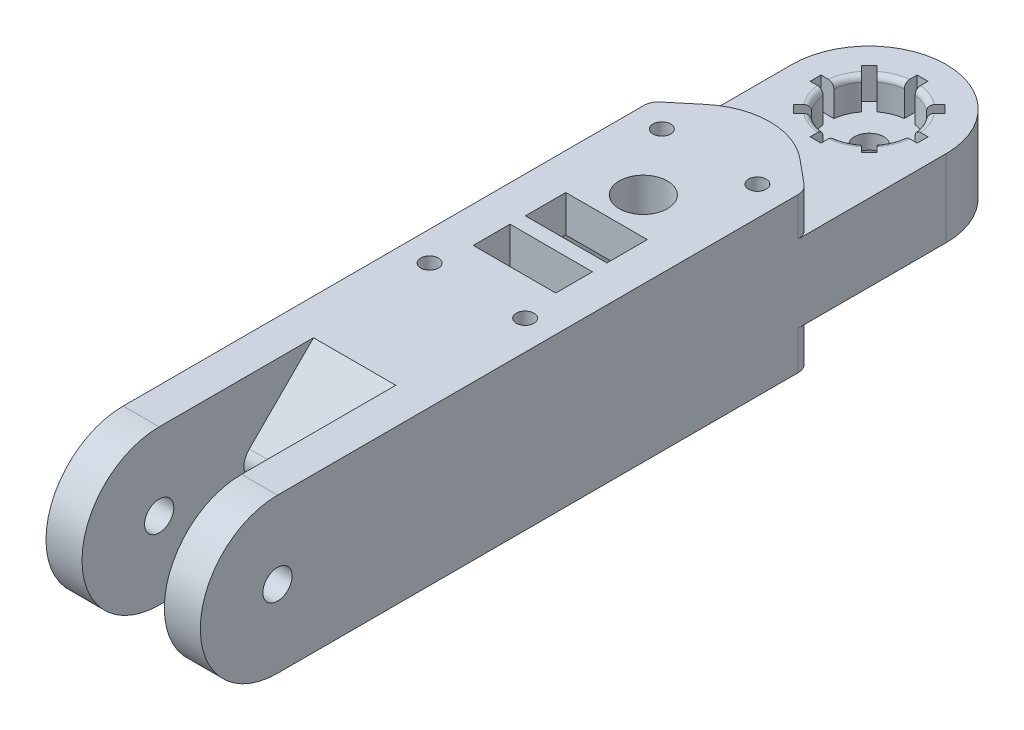
SolidWorks part; units mm, degrees
ref_plane "Front Plane" through (0, 0, 0) normal (0, 0, 1) x (1, 0, 0)
ref_plane "Top Plane" through (0, 0, 0) normal (0, 1, 0) x (1, 0, 0)
ref_plane "Right Plane" through (0, 0, 0) normal (1, 0, 0) x (0, 0, -1)
sketch "Sketch1" plane through (0, 0, 0) normal (0, 0, 1) x (1, 0, 0)
  line L1 (-21, 21) -> (21, 21)
  line L2 (-21, 21) -> (-21, -21)
  line L3 (-21, -21) -> (21, -21)
  line L4 (21, 21) -> (21, -21)
  line L5 (-21, 21) -> (21, -21) construction
  line L6 (-21, -21) -> (21, 21) construction
  point P0 (0, 0)
  dimension "D1" = 42
  dimension "D2" = 42
extrude "Boss-Extrude1" add sketch "Sketch1" along normal blind 140
ref_plane "Plane1" through (0, 0, 140) normal (0, 0, 1) x (1, 0, 0)
sketch "Sketch2" plane through (0, 0, 140) normal (0, 0, 1) x (1, 0, 0)
  line L0 (-21, -21) -> (21, -21) construction
  line L1 (-21, 21) -> (-11.2, 21)
  line L2 (-21, 21) -> (-21, -21)
  line L3 (-21, -21) -> (-11.2, -21)
  line L4 (-11.2, 21) -> (-11.2, -21)
  line L5 (21, 21) -> (-21, 21) construction
  line L6 (21, -21) -> (11.2, -21)
  line L7 (21, -21) -> (21, 21)
  line L8 (21, 21) -> (11.2, 21)
  line L9 (11.2, -21) -> (11.2, 21)
  dimension "D1" = 9.8
  dimension "D2" = 9.8
extrude "Boss-Extrude2" add sketch "Sketch2" along normal blind 21
ref_plane "Plane2" through (-11.2, 0, 0) normal (1, 0, 0) x (0, 0, -1)
sketch "Sketch3" plane through (-11.2, 0, 0) normal (1, 0, 0) x (0, 0, -1)
  line L0 (-161, -21) -> (-161, 21)
  arc A0 (-161, -21) -> (-161, 21) centre (-161, 0) cw
  dimension "D1" = 21
ref_plane "Plane3" through (0, -21, 0) normal (0, -1, 0) x (-1, 0, 0)
ref_plane "Plane4" through (11.2, 0, 0) normal (-1, 0, 0) x (0, 0, 1)
sketch "Sketch5" plane through (11.2, 0, 0) normal (-1, 0, 0) x (0, 0, 1)
  line L0 (161, 21) -> (161, -21)
  line L4 (140, 21) -> (140, -21)
  line L5 (140, -21) -> (161, -21)
  line L6 (161, -21) -> (161, 21)
  line L7 (161, 21) -> (140, 21)
  line L8 (140, 21) -> (140, -21)
  line L9 (140, -21) -> (161, -21)
  line L11 (161, 21) -> (140, 21)
  arc A0 (161, 21) -> (161, -21) centre (161, 0) cw
  dimension "D1" = 21
  dimension "D2" = 0
extrude "Boss-Extrude4" add sketch "Sketch5" against normal blind 9.8 contours A0 L0
extrude "Boss-Extrude5" add sketch "Sketch3" against normal blind 9.8
sketch "Sketch6" plane through (11.2, 0, 0) normal (-1, 0, 0) x (0, 0, 1)
  line L0 (161, -21) -> (161, 21) construction
  circle A0 centre (161, 0) radius 3.975
  dimension "D1" = 7.95
extrude "Cut-Extrude1" cut sketch "Sketch6" against normal through all
ref_plane "Plane5" through (-11.2, 0, 0) normal (1, 0, 0) x (0, 0, -1)
sketch "Sketch8" plane through (-11.2, 0, 0) normal (1, 0, 0) x (0, 0, -1)
  line L0 (-161, -21) -> (-161, 21) construction
  circle A0 centre (-161, 0) radius 3.975
  dimension "D1" = 7.95
extrude "Cut-Extrude2" cut sketch "Sketch8" against normal through all
ref_plane "Plane6" through (0, 0, 0) normal (0, 0, -1) x (-1, 0, 0)
sketch "Sketch9" plane through (0, 0, 0) normal (0, 0, -1) x (-1, 0, 0)
  line L0 (21, 21) -> (21, -21) construction
  line L1 (21, 10.5) -> (-21, 10.5)
  line L2 (21, 10.5) -> (21, -10.5)
  line L3 (21, -10.5) -> (-21, -10.5)
  line L4 (-21, 10.5) -> (-21, -10.5)
  line L5 (-21, -21) -> (-21, 21) construction
  line L6 (-21, 21) -> (21, 21) construction
  line L7 (21, -21) -> (-21, -21) construction
  dimension "D1" = 10.5
  dimension "D2" = 10.5
extrude "Boss-Extrude6" add sketch "Sketch9" along normal blind 21
ref_plane "Plane7" through (0, -10.5, 0) normal (0, -1, 0) x (-1, 0, 0)
sketch "Sketch10" plane through (0, -10.5, 0) normal (0, -1, 0) x (-1, 0, 0)
  line L0 (-21, 21) -> (21, 21)
  arc A0 (-21, 21) -> (21, 21) centre (0, 21) cw
  dimension "D1" = 21
extrude "Boss-Extrude7" add sketch "Sketch10" against normal blind 21
sketch "Sketch11" plane through (0, -10.5, 0) normal (0, -1, 0) x (-1, 0, 0)
  line L0 (21, 21) -> (-21, 21) construction
  circle A0 centre (0, 21) radius 11.35
  dimension "D1" = 22.7
extrude "Cut-Extrude3" cut sketch "Sketch11" against normal blind 8.5
ref_plane "Plane8" through (11.2, 0, 0) normal (-1, 0, 0) x (0, 0, 1)
sketch "Sketch16" plane through (11.2, 0, 0) normal (-1, 0, 0) x (0, 0, 1)
  line L0 (140, 21) -> (140, 0)
  line L1 (140, 21) -> (140, -21) construction
  line L2 (140, 0) -> (140, -21)
  line L3 (140, -21) -> (119, -21)
  line L4 (119, -21) -> (140, 0)
  line L5 (140, 21) -> (119, 21)
  line L6 (119, 21) -> (140, 0)
  line L7 (161, 0) -> (140, 0) construction
  dimension "D1" = 21
  dimension "D2" = 21
extrude "Cut-Extrude4" cut sketch "Sketch16" along normal blind 22.4 contours L0 L5 L6 | L2 L3 L4
fillet "Fillet1" radius 5 1 edges at (0, 0, 140)
ref_plane "Plane9" through (0, -10.5, 0) normal (0, -1, 0) x (-1, 0, 0)
ref_plane "Plane10" through (0, 10.5, 0) normal (0, 1, 0) x (1, 0, 0)
sketch "Sketch18" plane through (0, 10.5, 0) normal (0, 1, 0) x (1, 0, 0)
  line L0 (21, 21) -> (-21, 21) construction
  circle A0 centre (0, 21) radius 11.1605
  dimension "D1" = 22.321
extrude "Cut-Extrude5" cut sketch "Sketch18" against normal blind 8.5
sketch "Sketch19" plane through (0, -2, 0) normal (0, -1, 0) x (1, 0, 0)
  circle A0 centre (0, -21) radius 3.975
  dimension "D1" = 7.95
extrude "Cut-Extrude6" cut sketch "Sketch19" against normal blind 8.5
fillet "Fillet4" radius 1.5 1 edges at (11.35, -10.5, -21)
fillet "Fillet5" radius 1.5 1 edges at (-11.1605, 10.5, -21)
sketch "Sketch20" plane through (0, 10.5, 0) normal (0, 1, 0) x (1, 0, 0)
  line L1 (-1.48, 35.5655) -> (1.48, 35.5655)
  line L2 (-1.48, 35.5655) -> (-1.48, 31.7555)
  line L3 (-1.48, 31.7555) -> (1.48, 31.7555)
  line L4 (1.48, 35.5655) -> (1.48, 31.7555)
  line L5 (-1.48, 35.5655) -> (1.48, 31.7555) construction
  line L6 (-1.48, 31.7555) -> (1.48, 35.5655) construction
  circle A0 centre (0, 21) radius 12.6605 construction
  point P0 (0, 33.6605)
  dimension "D1" = 2.96
  dimension "D2" = 3.81
extrude "Cut-Extrude7" cut sketch "Sketch20" against normal blind 8.5
pattern_circular "CirPattern1" count 8 over 360 about axis through (0, 0, -21) along (0, 1, 0) of "Cut-Extrude7"
ref_plane "Plane11" through (0, 0, 0) normal (0, 1, 0) x (1, 0, 0)
mirror "Mirror1" about plane through (0, 0, 0) normal (0, 1, 0) of "CirPattern1", "Cut-Extrude7"
sketch "Sketch25" plane through (0, -21, 0) normal (0, -1, 0) x (1, 0, 0)
  line L0 (0, 0) -> (0, 119) construction
  line L2 (-21, 0) -> (21, 0) construction
  line L3 (17, 78.5) -> (-17, 78.5)
  line L4 (17, 78.5) -> (17, 29.5)
  line L5 (17, 29.5) -> (-17, 29.5)
  line L6 (-17, 78.5) -> (-17, 29.5)
  line L7 (17, 78.5) -> (-17, 29.5) construction
  line L8 (17, 29.5) -> (-17, 78.5) construction
  point P5 (0, 54)
  dimension "D1" = 34
  dimension "D2" = 49
  dimension "D3" = 54
extrude "Cut-Extrude11" cut sketch "Sketch25" against normal blind 32 contours L3 L6 L5 L4
sketch "Sketch26" plane through (0, -21, 0) normal (0, -1, 0) x (1, 0, 0)
  line L0 (0, 29.5) -> (0, 18.4) construction
  line L1 (17, 29.5) -> (-17, 29.5)
  line L2 (17, 29.5) -> (17, 26.5)
  line L3 (17, 26.5) -> (-17, 26.5)
  line L4 (-17, 29.5) -> (-17, 26.5)
  line L5 (-17, 26.5) -> (17, 26.5)
  line L6 (-17, 26.5) -> (-17, 18.4)
  line L7 (-17, 18.4) -> (17, 18.4)
  line L8 (17, 26.5) -> (17, 18.4)
  line M6 (17, 29.5) -> (-17, 29.5)
  line M7 (-21, 0) -> (21, 0)
  dimension "D1" = 3
  dimension "D2" = 8.1
extrude "Cut-Extrude12" cut sketch "Sketch26" against normal blind 27 contours L3 L0 L8 M7 | L0 L3 L2 M6 | L0 L1 L4 L5 | L0 L5 L6 M7 | L0 L6 L7 M7 | L0 L7 L8 M7
sketch "Sketch30" plane through (0, 6, 0) normal (0, -1, 0) x (1, 0, 0)
  line L0 (0, 29.5) -> (0, 18.4) construction
  line L1 (17, 29.5) -> (-17, 29.5) construction
  line L2 (-17, 18.4) -> (17, 18.4) construction
  line L3 (-17, 29.5) -> (-17, 18.4) construction
  circle A0 centre (-13, 22.4) radius 4
  circle A1 centre (-13, 22.4) radius 2.4
  dimension "D1" = 8
  dimension "D2" = 4.8
extrude "Cut-Extrude13" cut sketch "Sketch30" against normal through all contours A1
ref_plane "Plane12" through (0, 0, 0) normal (-1, 0, 0) x (0, 0, 1)
mirror "Mirror9" about plane through (0, 0, 0) normal (-1, 0, 0) of "Cut-Extrude13"
ref_plane "Plane13" through (0, 0, 54) normal (0, 0, 1) x (1, 0, 0)
sketch "Sketch32" plane through (0, 21, 0) normal (0, 1, 0) x (1, 0, 0)
  line L3 (0, 0) -> (0, -65.7087) construction
  line L4 (0, 17.6) -> (0, -17.6) construction
  line L10 (0, 0) -> (21, -17.4215)
  line L11 (21, -161) -> (21, 0) construction
  line L13 (-21, -161) -> (-21, 0) construction
  line L14 (-21, -17.4215) -> (0, 0)
  line L15 (0, 0) -> (-21, 0)
  line L16 (-21, 0) -> (-21, -17.4215)
  line L17 (0, 0) -> (21, 0)
  line L18 (21, 0) -> (21, -17.4215)
  line M13 (21, -161) -> (21, 0)
  line M14 (21, 0) -> (-21, 0)
  line M15 (-21, 0) -> (-21, -161)
fillet "Fillet10" radius 3 2 edges at (-17, -7.5, 18.4) (17, -7.5, 18.4)
ref_plane "Plane14" through (0, 0, 54) normal (0, 0, -1) x (-1, 0, 0)
mirror "Mirror12" about plane through (0, 0, 54) normal (0, 0, -1) of "Fillet10", "Mirror9", "Cut-Extrude13", "Cut-Extrude12"
extrude "Cut-Extrude16" cut sketch "Sketch32" against normal blind 10.5 contours L14 M15 M14 | L10 M14 M13
fillet "Fillet12" radius 20 1 edges at (0, 15.75, 0)
mirror "Mirror13" about plane through (0, 0, 0) normal (0, 1, 0) of "Fillet12", "Cut-Extrude16"
fillet "Fillet13" radius 4 4 edges at (-21, 15.75, 17.4215) (-21, -15.75, 17.4215) (21, -15.75, 17.4215) (21, 15.75, 17.4215)
sketch "Sketch33" plane through (0, 11, 0) normal (0, -1, 0) x (1, 0, 0)
  line L0 (-17, 78.5) -> (-17, 65.5) construction
  line L1 (-17, 78.5) -> (-17, 29.5) construction
  line L2 (0, 78.5) -> (0, 29.5) construction
  line L3 (17, 78.5) -> (-17, 78.5) construction
  line L4 (17, 29.5) -> (-17, 29.5) construction
  line L5 (-17, 65.5) -> (17, 65.5) construction
  line L7 (17, 86.6) -> (17, 21.4) construction
  line L8 (-11.225, 65.5) -> (11.225, 65.5)
  line L9 (-11.225, 65.5) -> (-11.225, 75.5)
  line L10 (-11.225, 75.5) -> (11.225, 75.5)
  line L11 (11.225, 75.5) -> (11.225, 65.5)
  line L12 (-17, 47) -> (17, 47) construction
  line L13 (17, 78.5) -> (17, 29.5) construction
  line L15 (11.1, 50.44) -> (-11.1, 50.44)
  line L16 (11.1, 50.44) -> (11.1, 61.44)
  line L17 (11.1, 61.44) -> (-11.1, 61.44)
  line L18 (-11.1, 50.44) -> (-11.1, 61.44)
  circle A0 centre (0, 40.44) radius 6.56
  point P12 (0, 29.5)
  point P17 (0, 65.5)
  point P26 (0, 50.44)
  dimension "D5" = 13.12
  dimension "D1" = 13
  dimension "D2" = 22.45
  dimension "D3" = 10
  dimension "D4" = 17.5
  dimension "D6" = 21
  dimension "D7" = 22.2
  dimension "D8" = 11
extrude "Cut-Extrude17" cut sketch "Sketch33" against normal through all
sketch "Sketch34" plane through (21, 0, 0) normal (1, 0, 0) x (0, 0, -1)
  circle A0 centre (-161, 0) radius 12.5
  dimension "D1" = 25
